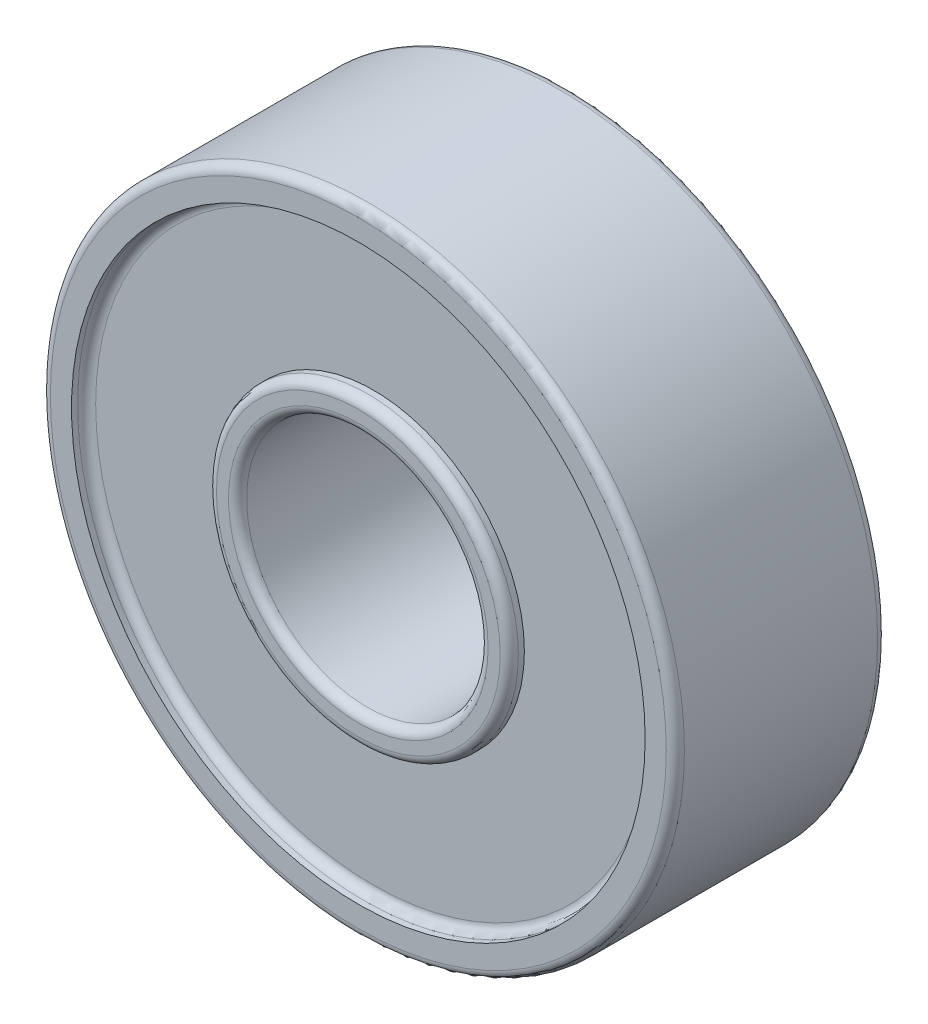
SolidWorks part; units mm, degrees
ref_plane "Alzado" through (0, 0, 0) normal (0, 0, 1) x (1, 0, 0)
ref_plane "Planta" through (0, 0, 0) normal (0, 1, 0) x (1, 0, 0)
ref_plane "Vista lateral" through (0, 0, 0) normal (1, 0, 0) x (0, 0, -1)
sketch "Croquis1" plane through (0, 0, 0) normal (0, 0, 1) x (1, 0, 0)
  circle A0 centre (0, 0) radius 4
  circle A1 centre (0, 0) radius 5
  dimension "D1" = 8
  dimension "D2" = 10
extrude "Saliente-Extruir1" add sketch "Croquis1" along normal blind 7
sketch "Croquis2" plane through (0, 0, 7) normal (0, 0, 1) x (1, 0, 0)
  circle A0 centre (0, 0) radius 9.5
  circle A1 centre (0, 0) radius 5
  circle A2 centre (0, 0) radius 5 construction
  dimension "D1" = 19
extrude "Saliente-Extruir2" add sketch "Croquis2" against normal blind 6 from offset 0.5 offset against normal yes
sketch "Croquis3" plane through (0, 0, 7) normal (0, 0, 1) x (1, 0, 0)
  circle A0 centre (0, 0) radius 9.5
  circle A1 centre (0, 0) radius 10.5
  circle A2 centre (0, 0) radius 9.5 construction
  dimension "D1" = 21
extrude "Saliente-Extruir3" add sketch "Croquis3" against normal blind 7
fillet "Redondeo1" radius 0.3 8 edges at (4, 0, 0) (4, 0, 7) (5, 0, 0) (5, 0, 7) (9.5, 0, 6.5) (10.5, 0, 7) (9.5, 0, 0) (10.5, 0, 0)
